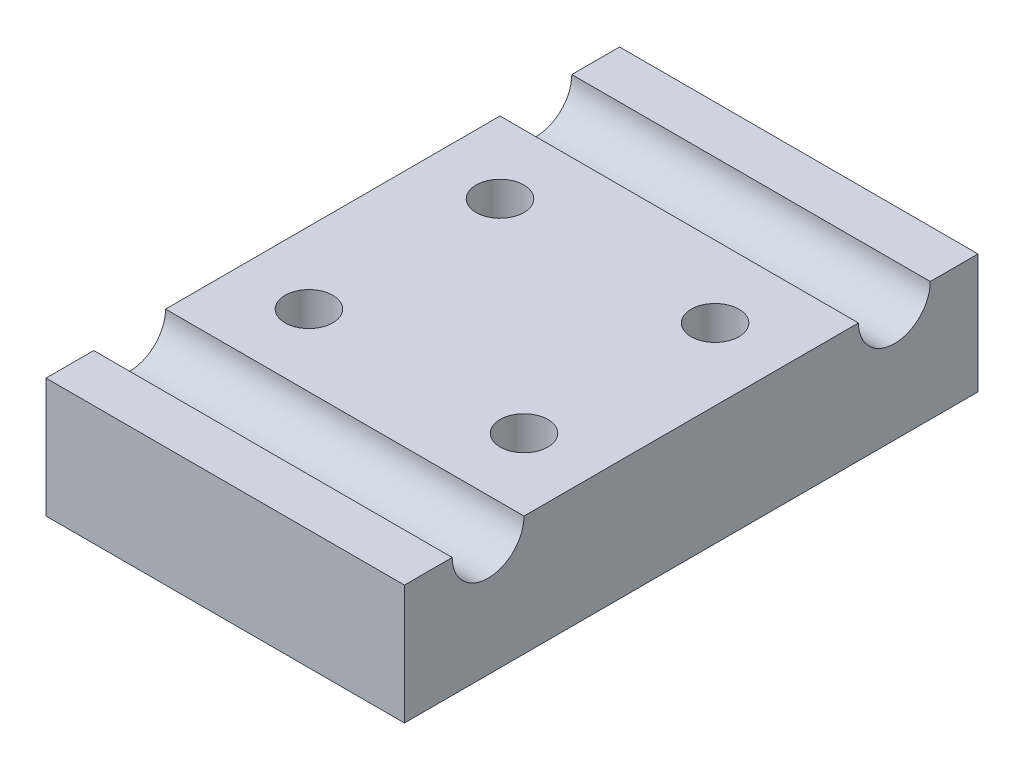
SolidWorks part; units mm, degrees
ref_plane "前视基准面" through (0, 0, 0) normal (0, 0, 1) x (1, 0, 0)
ref_plane "上视基准面" through (0, 0, 0) normal (0, 1, 0) x (1, 0, 0)
ref_plane "右视基准面" through (0, 0, 0) normal (1, 0, 0) x (0, 0, -1)
other "Configuration Table"
sketch "草图1" plane through (0, 0, 0) normal (0, 0, 1) x (1, 0, 0)
  line L1 (0, 0) -> (30, 0)
  line L2 (0, 0) -> (0, 10)
  line L3 (0, 10) -> (30, 10)
  line L4 (30, 0) -> (30, 10)
extrude "凸台-拉伸1" add sketch "草图1" along normal blind 48
sketch "草图3" plane through (0, 0, 0) normal (-1, 0, 0) x (0, 0, 1)
  line L0 (48, 10) -> (0, 10) construction
  line L1 (0, 10) -> (0, 0) construction
  circle A0 centre (7, 10) radius 3.005
  circle A1 centre (41, 10) radius 3.005
  dimension "D1" = 34
  dimension "D2" = 7
extrude "切除-拉伸1" cut sketch "草图3" against normal blind 48
sketch "草图4" plane through (0, 10, 0) normal (0, 1, 0) x (1, 0, 0)
  line L0 (0, -37.995) -> (30, -37.995) construction
  line L1 (30, -10.005) -> (0, -10.005) construction
  line L2 (30, -37.995) -> (30, -10.005) construction
  circle A0 centre (24, -31.995) radius 2
  circle A3 centre (6, -31.995) radius 2
  circle A4 centre (24, -16.005) radius 2
  circle A7 centre (6, -16.005) radius 2
  dimension "D1" = 4
  dimension "D2" = 6
  dimension "D4" = 6
  dimension "D3" = 6
extrude "切除-拉伸2" cut sketch "草图4" against normal through all
